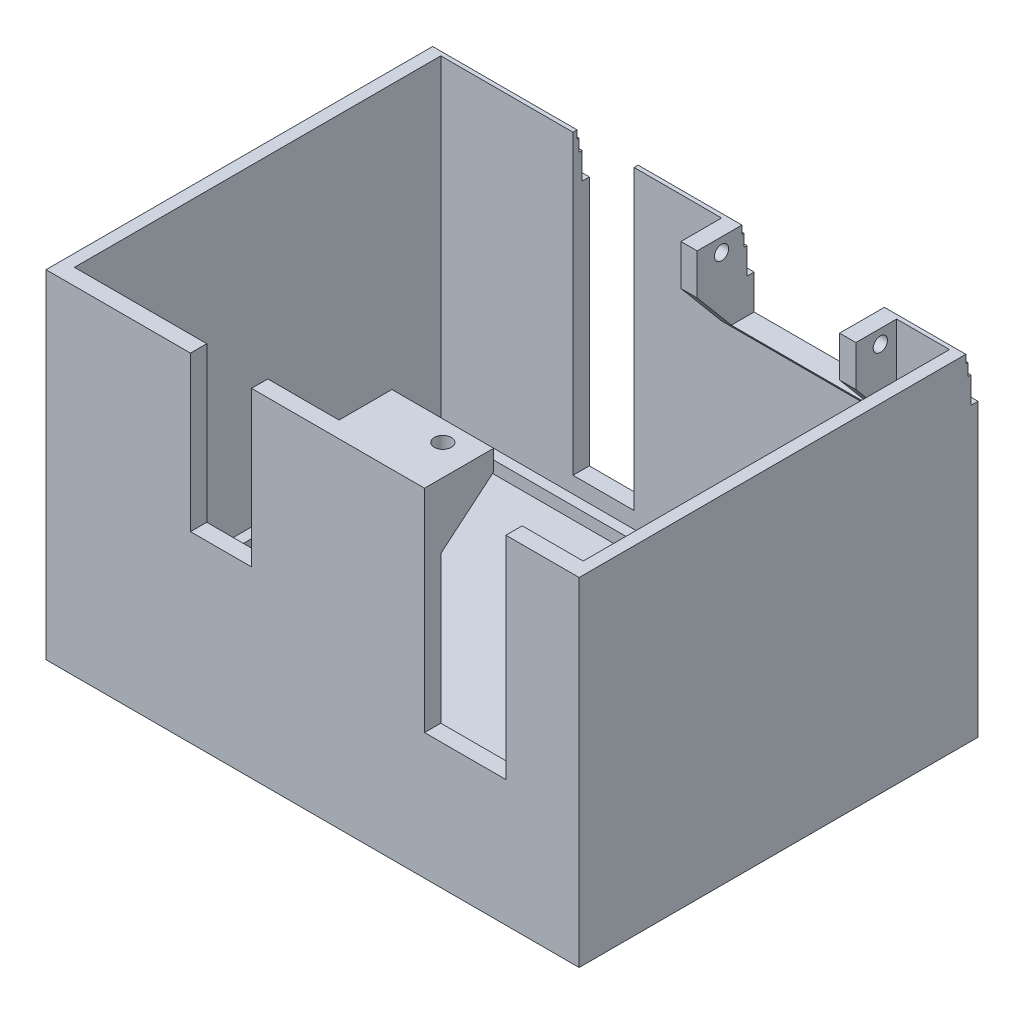
SolidWorks part; units mm, degrees
ref_plane "Front Plane" through (0, 0, 0) normal (0, 0, 1) x (1, 0, 0)
ref_plane "Top Plane" through (0, 0, 0) normal (0, 1, 0) x (1, 0, 0)
ref_plane "Right Plane" through (0, 0, 0) normal (1, 0, 0) x (0, 0, -1)
sketch "Sketch1" plane through (0, 0, 0) normal (0, 1, 0) x (1, 0, 0)
  line L1 (62.5, -45) -> (-62.5, -45)
  line L2 (62.5, -45) -> (62.5, 45)
  line L3 (62.5, 45) -> (-62.5, 45)
  line L4 (-62.5, -45) -> (-62.5, 45)
  line L5 (62.5, -45) -> (-62.5, 45) construction
  line L6 (62.5, 45) -> (-62.5, -45) construction
  line L7 (65.5, -49) -> (-65.5, -49)
  line L8 (65.5, -49) -> (65.5, 49)
  line L9 (65.5, 49) -> (-65.5, 49)
  line L10 (-65.5, -49) -> (-65.5, 49)
  line L11 (65.5, -49) -> (-65.5, 49) construction
  line L12 (65.5, 49) -> (-65.5, -49) construction
  point P0 (0, 0)
  point P5 (0, 0)
  dimension "D4" = 4
  dimension "D1" = 125
  dimension "D2" = 90
  dimension "D3" = 3
extrude "Boss-Extrude1" add sketch "Sketch1" along normal blind 80
sketch "Sketch2" plane through (0, 0, 0) normal (0, -1, 0) x (1, 0, 0)
  line L1 (65.5, -49) -> (-65.5, -49)
  line L2 (65.5, -49) -> (65.5, 49)
  line L3 (65.5, 49) -> (-65.5, 49)
  line L4 (-65.5, -49) -> (-65.5, 49)
extrude "Boss-Extrude2" add sketch "Sketch2" along normal blind 3
sketch "Sketch4" plane through (0, 0, 0) normal (0, 1, 0) x (1, 0, 0)
  line L1 (-62.5, 45) -> (62.5, 45)
  line L2 (-62.5, 45) -> (-62.5, -45)
  line L3 (-62.5, -45) -> (62.5, -45)
  line L4 (62.5, 45) -> (62.5, -45)
  line L5 (59.5, -42) -> (-60, -42)
  line L6 (59.5, -42) -> (59.5, 42.5)
  line L7 (59.5, 42.5) -> (-60, 42.5)
  line L8 (-60, -42) -> (-60, 42.5)
  dimension "D1" = 2.5
  dimension "D2" = 2.5
  dimension "D3" = 3
  dimension "D4" = 3
extrude "Boss-Extrude3" add sketch "Sketch4" along normal blind 3
sketch "Sketch5" plane through (0, 0, -49) normal (0, 0, -1) x (-1, 0, 0)
  line L0 (-65.5, 80) -> (65.5, 80) construction
  line L1 (15, 80) -> (30, 80)
  line L2 (15, 80) -> (15, 7)
  line L3 (15, 7) -> (30, 7)
  line L4 (30, 80) -> (30, 7)
  line L5 (15, 80) -> (30, 7) construction
  line L6 (15, 7) -> (30, 80) construction
  line L7 (62.5, 74.3372) -> (62.5, 12.8298) construction
  line L8 (65.5, 80) -> (65.5, -3) construction
  line L9 (65.5, -3) -> (-65.5, -3) construction
  point P0 (22.5, 43.5)
  dimension "D1" = 3
  dimension "D2" = 40
  dimension "D3" = 15
  dimension "D4" = 10
extrude "Cable Cut Top" cut sketch "Sketch5" against normal up to surface (4 mm away) up to face at (0, 41.5, -45)
sketch "Sketch6" plane through (0, 0, 45) normal (0, 0, -1) x (-1, 0, 0)
  line L0 (62.5, 80) -> (-62.5, 80) construction
  line L1 (-27.5, 28) -> (-47.5, 28)
  line L2 (-27.5, 28) -> (-27.5, 80)
  line L3 (-27.5, 80) -> (-47.5, 80)
  line L4 (-47.5, 28) -> (-47.5, 80)
  line L5 (-27.5, 28) -> (-47.5, 80) construction
  line L6 (-27.5, 80) -> (-47.5, 28) construction
  line L7 (62.5, 3) -> (-62.5, 3) construction
  line L8 (-62.5, 80) -> (-62.5, 3) construction
  point P0 (-37.5, 54)
  dimension "D1" = 25
  dimension "D2" = 20
  dimension "D3" = 25
extrude "Cable Cut Bottom Right" cut sketch "Sketch6" against normal up to next
sketch "Sketch10" plane through (0, 0, 49) normal (0, 0, 1) x (1, 0, 0)
  line L0 (-65.5, 80) -> (27.5, 80) construction
  line L1 (-30, 80) -> (-15, 80)
  line L2 (-30, 80) -> (-30, 42)
  line L3 (-30, 42) -> (-15, 42)
  line L4 (-15, 80) -> (-15, 42)
  line L5 (-30, 7) -> (-30, 80) construction
  line L6 (-15, 80) -> (-15, 7) construction
  line L8 (65.5, -3) -> (-65.5, -3) construction
  dimension "D1" = 45
extrude "Cable Cut Bottom Left" cut sketch "Sketch10" against normal up to surface (4 mm away) up to face at (18.75, 47.75, 45)
sketch "Sketch7" plane through (0, 0, -45) normal (0, 0, 1) x (1, 0, 0)
  line L0 (62.5, 80) -> (-15, 80) construction
  line L6 (10.5, 80) -> (45.5, 80)
  line L7 (10.5, 80) -> (10.5, 60)
  line L8 (10.5, 60) -> (45.5, 60)
  line L9 (45.5, 80) -> (45.5, 60)
  dimension "D1" = 20
  dimension "D2" = 20
  dimension "D3" = 35
extrude "Schanier Cut" cut sketch "Sketch7" against normal up to next
sketch "Sketch8" plane through (0, 0, -45) normal (0, 0, 1) x (1, 0, 0)
  line L0 (45.5, 60) -> (45.5, 80) construction
  line L1 (10.5, 80) -> (6.5, 80)
  line L2 (10.5, 80) -> (10.5, 70)
  line L3 (10.5, 70) -> (6.5, 70)
  line L4 (6.5, 80) -> (6.5, 70)
  line L13 (45.5, 80) -> (49.5, 80)
  line L14 (45.5, 80) -> (45.5, 70)
  line L15 (45.5, 70) -> (49.5, 70)
  line L16 (49.5, 80) -> (49.5, 70)
  dimension "D1" = 4
  dimension "D3" = 10
  dimension "D5" = 4
extrude "Schanier" add sketch "Sketch8" along normal blind 10
sketch "Skizze2" plane through (6.5, 0, 0) normal (-1, 0, 0) x (0, 0, 1)
  line L0 (-35, 70) -> (-45, 70)
  line L1 (-45, 70) -> (-45, 58.0825)
  line L2 (-45, 58.0825) -> (-35, 70)
  dimension "D1" = 40
extrude "3D Printer Support" add sketch "Skizze2" against normal up to vertex (43 mm away) up to point (49.5, 70, -35)
sketch "Skizze3" plane through (0, 0, -45) normal (0, 0, -1) x (-1, 0, 0)
  line L5 (-45.5, 60) -> (-10.5, 60)
  line L6 (-45.5, 60) -> (-45.5, 70)
  line L7 (-45.5, 70) -> (-10.5, 70)
  line L8 (-10.5, 60) -> (-10.5, 70)
extrude "Schnitt-Linear austragen1" cut sketch "Skizze3" against normal blind 20
sketch "Skizze5" plane through (6.5, 0, 0) normal (-1, 0, 0) x (0, 0, 1)
  line L1 (-35, 80) -> (-45, 80) construction
  line L2 (-49, 60) -> (-49, 80) construction
  circle A0 centre (-41, 76.6459) radius 1.75
  point P5 (-40, 80)
  dimension "D3" = 3.5
  dimension "D1" = 8
  dimension "D2" = 3.5
extrude "Schnitt-Linear austragen3" cut sketch "Skizze5" against normal up to surface (43 mm away) up to face at (49.5, 72.0206, -40)
ref_plane "Ebene1" through (27.5, 0, 0) normal (1, 0, 0) x (0, 0, -1)
sketch "Skizze9" plane through (27.5, 0, 0) normal (1, 0, 0) x (0, 0, -1)
  line L0 (-45, 80) -> (-32, 80)
  line L1 (-32, 80) -> (-32, 75)
  line L2 (-32, 75) -> (-45, 64.0917)
  line L3 (-45, 64.0917) -> (-45, 80)
  line L4 (-45, 28) -> (-45, 80) construction
  line L5 (-49, 80) -> (-45, 80) construction
  line L6 (-39, 80) -> (-39, 58.0539) construction
  line L7 (-42.2981, 66) -> (6.0171, 66) construction
  dimension "D1" = 13
  dimension "D2" = 50
  dimension "D3" = 5
  dimension "D4" = 14
  dimension "D5" = 6
extrude "Aufsatz-Linear austragen2" add sketch "Skizze9" against normal blind 25
sketch "Skizze10" plane through (0, 80, 0) normal (0, 1, 0) x (1, 0, 0)
  line L0 (27.5, -49) -> (27.5, -32) construction
  line L1 (2.5, -45) -> (27.5, -45) construction
  line L2 (65.5, -49) -> (65.5, 49) construction
  circle A0 centre (20, -37) radius 2.1
  dimension "D1" = 4.2
  dimension "D2" = 8
  dimension "D3" = 7.5
  dimension "D4" = 45.5
extrude "Schnitt-Linear austragen4" cut sketch "Skizze10" against normal up to vertex up to point (2.5, 64.0917, 45)
sketch "Sketch9" plane through (-65.5, 0, 0) normal (-1, 0, 0) x (0, 0, 1)
  line L0 (-46, 78) -> (-46.5, 78)
  line L1 (-49, 80) -> (-46, 80)
  line L2 (-49, 68.5) -> (-49, 80)
  line L3 (-47.25, 75) -> (-47.25, 68.5)
  line L4 (-46, 80) -> (-46, 78)
  line L5 (-47.25, 68.5) -> (-49, 68.5)
  line L6 (-49, 80) -> (-49, -3) construction
  line L7 (-46.5, 78) -> (-46.5, 75)
  line L8 (-46.5, 75) -> (-47.25, 75)
  dimension "D1" = 1.75
  dimension "D2" = 2
  dimension "D3" = 6.5
  dimension "D4" = 3
  dimension "D5" = 0.5
  dimension "D6" = 3
extrude "Cut-Extrude4" cut sketch "Sketch9" against normal up to surface (131 mm away) up to face at (65.5, 38.5, 0)
